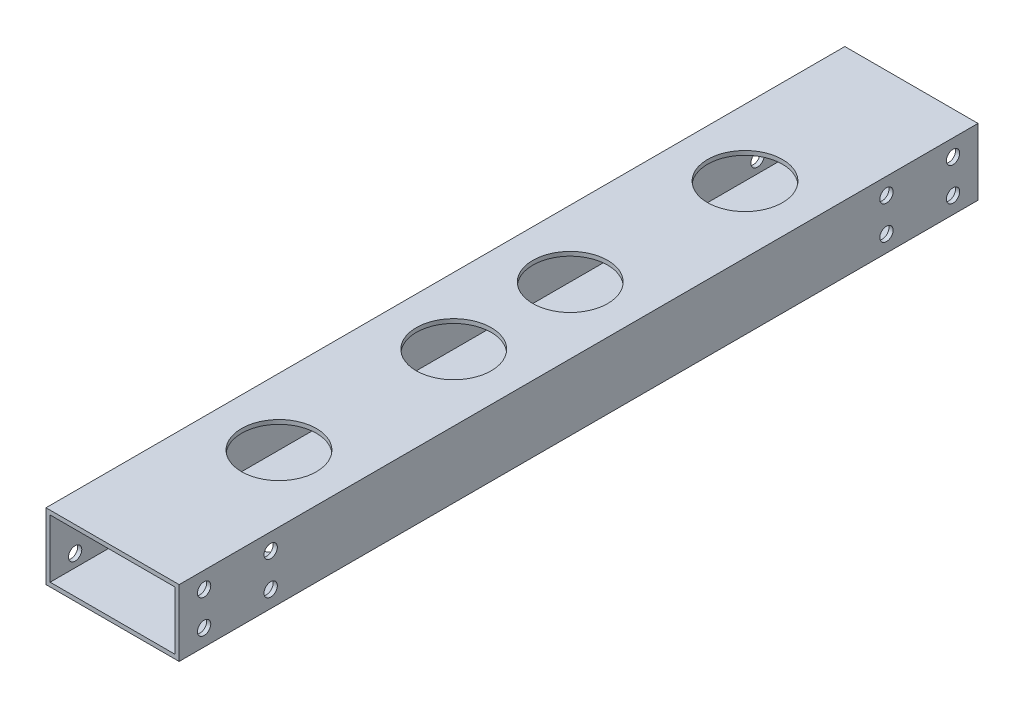
SolidWorks part; units mm, degrees
material "1060 Alloy"
ref_plane "Front Plane" through (0, 0, 0) normal (0, 0, 1) x (1, 0, 0)
ref_plane "Top Plane" through (0, 0, 0) normal (0, 1, 0) x (1, 0, 0)
ref_plane "Right Plane" through (0, 0, 0) normal (1, 0, 0) x (0, 0, -1)
sketch "Sketch2" plane through (0, 0, 0) normal (0, 0, 1) x (1, 0, 0)
  line L1 (-25.4, -12.7) -> (25.4, -12.7)
  line L2 (-25.4, -12.7) -> (-25.4, 12.7)
  line L3 (-25.4, 12.7) -> (25.4, 12.7)
  line L4 (25.4, -12.7) -> (25.4, 12.7)
  line L5 (-23.8125, -11.1125) -> (23.8125, -11.1125)
  line L6 (-23.8125, -11.1125) -> (-23.8125, 11.1125)
  line L7 (-23.8125, 11.1125) -> (23.8125, 11.1125)
  line L8 (23.8125, -11.1125) -> (23.8125, 11.1125)
  point P11 (0, -11.1125)
  point P13 (-23.8125, 0)
  dimension "D1" = 25.4
  dimension "D2" = 50.8
  dimension "D3" = 1.5875
  dimension "D4" = 1.5875
  dimension "D5" = 1.5875
  dimension "D6" = 1.5875
extrude "Boss-Extrude1" add sketch "Sketch2" along normal mid plane 304.8
sketch "Sketch3" plane through (0, 12.7, 0) normal (0, 1, 0) x (1, 0, 0)
  line L0 (-25.4, 0) -> (25.4, 0) construction
  line L1 (-25.4, -152.4) -> (-25.4, 152.4) construction
  line L2 (25.4, -152.4) -> (25.4, 152.4) construction
  circle A0 centre (0, -88.9) radius 14.2875
  circle A3 centre (0, -22.225) radius 14.2875
  circle A4 centre (0, 22.225) radius 14.2875
  circle A5 centre (0, 88.9) radius 14.2875
  dimension "D1" = 28.575
  dimension "D2" = 25.4
  dimension "D3" = 88.9
  dimension "D4" = 22.225
extrude "Cut-Extrude1" cut sketch "Sketch3" against normal through all
sketch "Sketch4" plane through (-25.4, 0, 0) normal (-1, 0, 0) x (0, 0, 1)
  line L0 (0, 12.7) -> (0, -12.7) construction
  line L1 (152.4, 12.7) -> (-152.4, 12.7) construction
  line L2 (152.4, -12.7) -> (-152.4, -12.7) construction
  line L3 (-107.95, 12.7) -> (-107.95, -12.7) construction
  line L4 (-152.4, 12.7) -> (-152.4, -12.7) construction
  circle A0 centre (-142.875, 6.35) radius 2.54
  circle A1 centre (-142.875, -6.35) radius 2.54
  circle A2 centre (-117.475, 6.35) radius 2.54
  circle A3 centre (-117.475, -6.35) radius 2.54
  circle A4 centre (117.475, -6.35) radius 2.54
  circle A5 centre (117.475, 6.35) radius 2.54
  circle A6 centre (142.875, -6.35) radius 2.54
  circle A7 centre (142.875, 6.35) radius 2.54
  dimension "D2" = 5.08
  dimension "D1" = 44.45
  dimension "D3" = 6.35
  dimension "D4" = 9.525
  dimension "D5" = 9.525
  dimension "D6" = 6.35
extrude "Cut-Extrude2" cut sketch "Sketch4" against normal through all both and the other way through all
